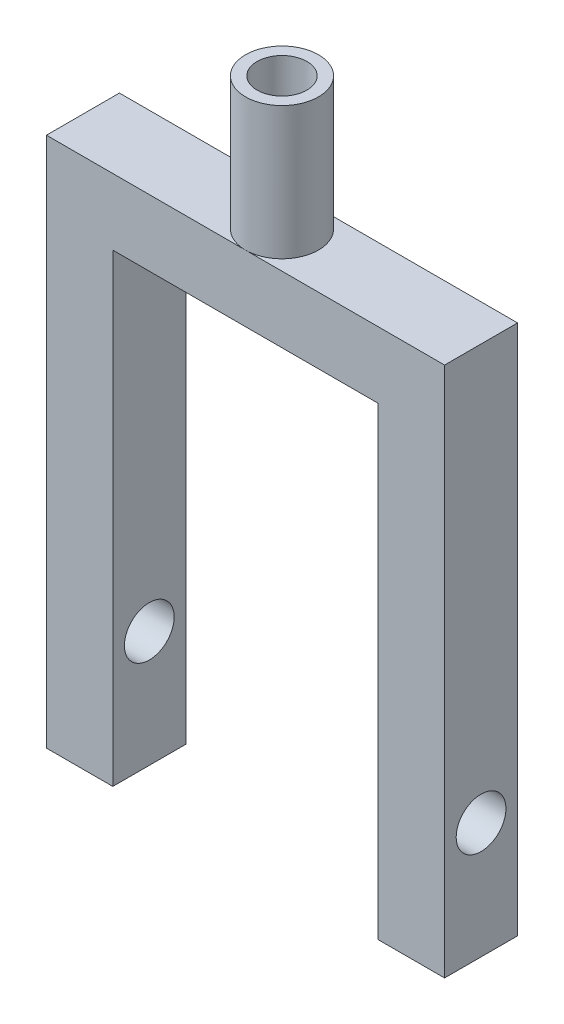
SolidWorks part; units mm, degrees
ref_plane "Front Plane" through (0, 0, 0) normal (0, 0, 1) x (1, 0, 0)
ref_plane "Top Plane" through (0, 0, 0) normal (0, 1, 0) x (1, 0, 0)
ref_plane "Right Plane" through (0, 0, 0) normal (1, 0, 0) x (0, 0, -1)
sketch "Sketch1" plane through (0, 0, 0) normal (0, 1, 0) x (1, 0, 0)
  circle A0 centre (0, 0) radius 6.985
  dimension "D1" = 13.97
extrude "Boss-Extrude1" add sketch "Sketch1" against normal blind 25.4
sketch "Sketch3" plane through (0, 0, 0) normal (0, 1, 0) x (1, 0, 0)
  circle A0 centre (0, 0) radius 4.7625
  circle A1 centre (0, 0) radius 6.985 construction
  dimension "D1" = 9.525
extrude "Cut-Extrude1" cut sketch "Sketch3" against normal blind 63.5
sketch "Sketch4" plane through (0, 0, 0) normal (0, 1, 0) x (1, 0, 0)
  line L0 (6.985, 0) -> (8.8102, 0) construction
  circle A0 centre (0, 0) radius 6.985 construction
  dimension "D1" = 1.8252
sketch "Sketch5" plane through (0, -25.4, 0) normal (0, -1, 0) x (-1, 0, 0)
  line L1 (38.1, -6.985) -> (-38.1, -6.985)
  line L2 (38.1, -6.985) -> (38.1, 6.985)
  line L3 (38.1, 6.985) -> (-38.1, 6.985)
  line L4 (-38.1, -6.985) -> (-38.1, 6.985)
  line L5 (38.1, -6.985) -> (-38.1, 6.985) construction
  line L6 (38.1, 6.985) -> (-38.1, -6.985) construction
  circle A0 centre (0, 0) radius 4.7625 construction
  point P0 (0, 0)
  dimension "D1" = 76.2
  dimension "D2" = 13.97
extrude "Boss-Extrude2" add sketch "Sketch5" along normal blind 101.6
sketch "Sketch6" plane through (0, 0, -6.985) normal (0, 0, -1) x (-1, 0, 0)
  line L0 (0, -25.4) -> (-38.1, -25.4) construction
  line L1 (25.4, -38.1) -> (-25.4, -38.1)
  line L2 (25.4, -38.1) -> (25.4, -127)
  line L3 (25.4, -127) -> (-25.4, -127)
  line L4 (-25.4, -38.1) -> (-25.4, -127)
  line L5 (25.4, -38.1) -> (-25.4, -127) construction
  line L6 (25.4, -127) -> (-25.4, -38.1) construction
  line L7 (38.1, -127) -> (38.1, -25.4) construction
  line L8 (38.1, -127) -> (-38.1, -127) construction
  point P0 (0, -64.4831)
  point P14 (0, -82.55)
  dimension "D1" = 50.8
  dimension "D3" = 12.7
  dimension "D4" = 38.1
extrude "Cut-Extrude2" cut sketch "Sketch6" against normal through all
sketch "Sketch7" plane through (0, 0, 0) normal (0, 1, 0) x (1, 0, 0)
  circle A0 centre (0, 0) radius 4.7625
  dimension "D1" = 9.525
extrude "Cut-Extrude3" cut sketch "Sketch7" against normal through all
sketch "Sketch8" plane through (25.4, 0, 0) normal (-1, 0, 0) x (0, 0, 1)
  line L0 (6.985, -38.1) -> (-6.985, -38.1) construction
  line L1 (-6.985, -38.1) -> (-6.985, -127) construction
  circle A0 centre (0, -104.775) radius 4.7625
  dimension "D1" = 9.525
  dimension "D2" = 66.675
  dimension "D3" = 6.985
extrude "Cut-Extrude4" cut sketch "Sketch8" against normal blind 19.05 and the other way through all
